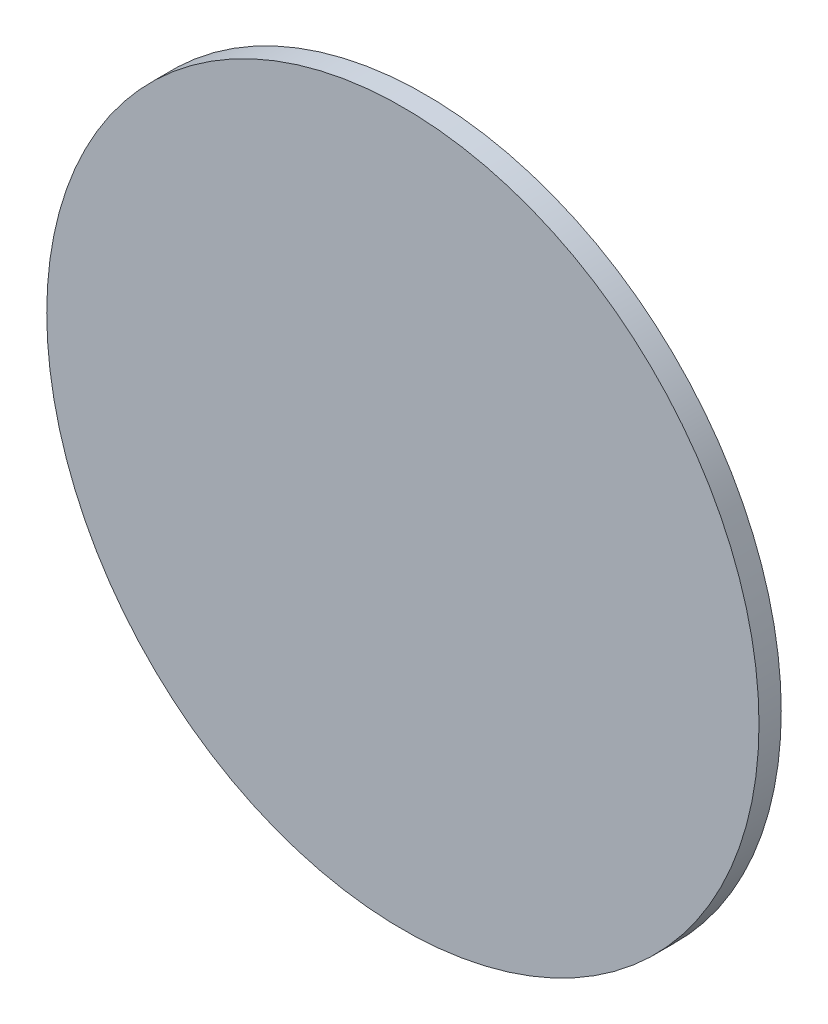
SolidWorks part; units mm, degrees
material "A-Glass Fiber"
ref_plane "Front Plane" through (0, 0, 0) normal (0, 0, 1) x (1, 0, 0)
ref_plane "Top Plane" through (0, 0, 0) normal (0, 1, 0) x (1, 0, 0)
ref_plane "Right Plane" through (0, 0, 0) normal (1, 0, 0) x (0, 0, -1)
sketch "Sketch1" plane through (0, 0, 0) normal (0, 0, 1) x (1, 0, 0)
  circle A0 centre (0, 0) radius 160
extrude "Boss-Extrude1" add sketch "Sketch1" along normal blind 10
